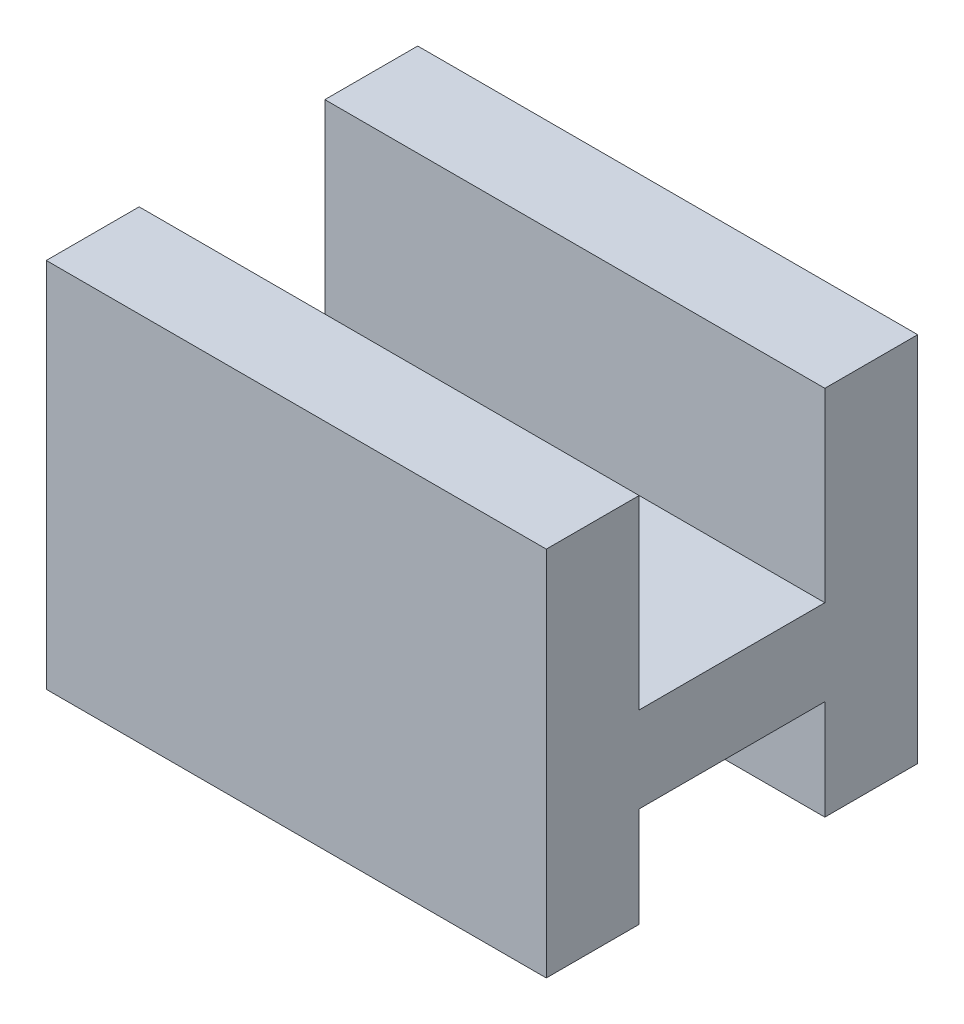
SolidWorks part; units mm, degrees
ref_plane "前基準面" through (0, 0, 0) normal (0, 0, 1) x (1, 0, 0)
ref_plane "上基準面" through (0, 0, 0) normal (0, 1, 0) x (1, 0, 0)
ref_plane "右基準面" through (0, 0, 0) normal (1, 0, 0) x (0, 0, -1)
sketch "草圖1" plane through (0, 0, 0) normal (0, 0, 1) x (1, 0, 0)
  line L1 (-17.5, 13) -> (17.5, 13)
  line L2 (-17.5, 13) -> (-17.5, -13)
  line L3 (-17.5, -13) -> (17.5, -13)
  line L4 (17.5, 13) -> (17.5, -13)
  line L5 (-17.5, 13) -> (17.5, -13) construction
  line L6 (-17.5, -13) -> (17.5, 13) construction
  point P0 (0, 0)
  dimension "D1" = 35
  dimension "D2" = 26
extrude "填料-伸長1" add sketch "草圖1" along normal blind 26
sketch "草圖3" plane through (-17.5, 0, 0) normal (-1, 0, 0) x (0, 0, 1)
  line L0 (26, 13) -> (0, 13) construction
  line L1 (6.5, 13) -> (19.5, 13)
  line L2 (6.5, 13) -> (6.5, 0)
  line L3 (6.5, 0) -> (19.5, 0)
  line L4 (19.5, 13) -> (19.5, 0)
  line L5 (26, -13) -> (0, -13) construction
  line L6 (6.5, -13) -> (19.5, -13)
  line L7 (6.5, -13) -> (6.5, -6)
  line L8 (6.5, -6) -> (19.5, -6)
  line L9 (19.5, -13) -> (19.5, -6)
  line L11 (13, 15.604) -> (13, -16.2487) construction
  line L12 (26, 13) -> (26, -13) construction
  line L13 (0, 13) -> (0, -13) construction
  point P12 (13, 13)
  point P15 (11.3488, 15.604)
  dimension "D1" = 13
  dimension "D2" = 13
  dimension "D3" = 7
  dimension "D4" = 13
extrude "除料-伸長1" cut sketch "草圖3" against normal blind 43
sketch "草圖5" plane through (0, 13, 0) normal (0, 1, 0) x (1, 0, 0)
  line L0 (17.5, 0) -> (-10.5, -26)
  line L1 (17.5, -26) -> (-17.5, -26) construction
  line L2 (-17.5, -26) -> (-17.5, -19.5) construction
  line L3 (-10.5, -26) -> (17.5, -26)
  line L4 (17.5, 0) -> (17.5, -26)
  dimension "D1" = 7
